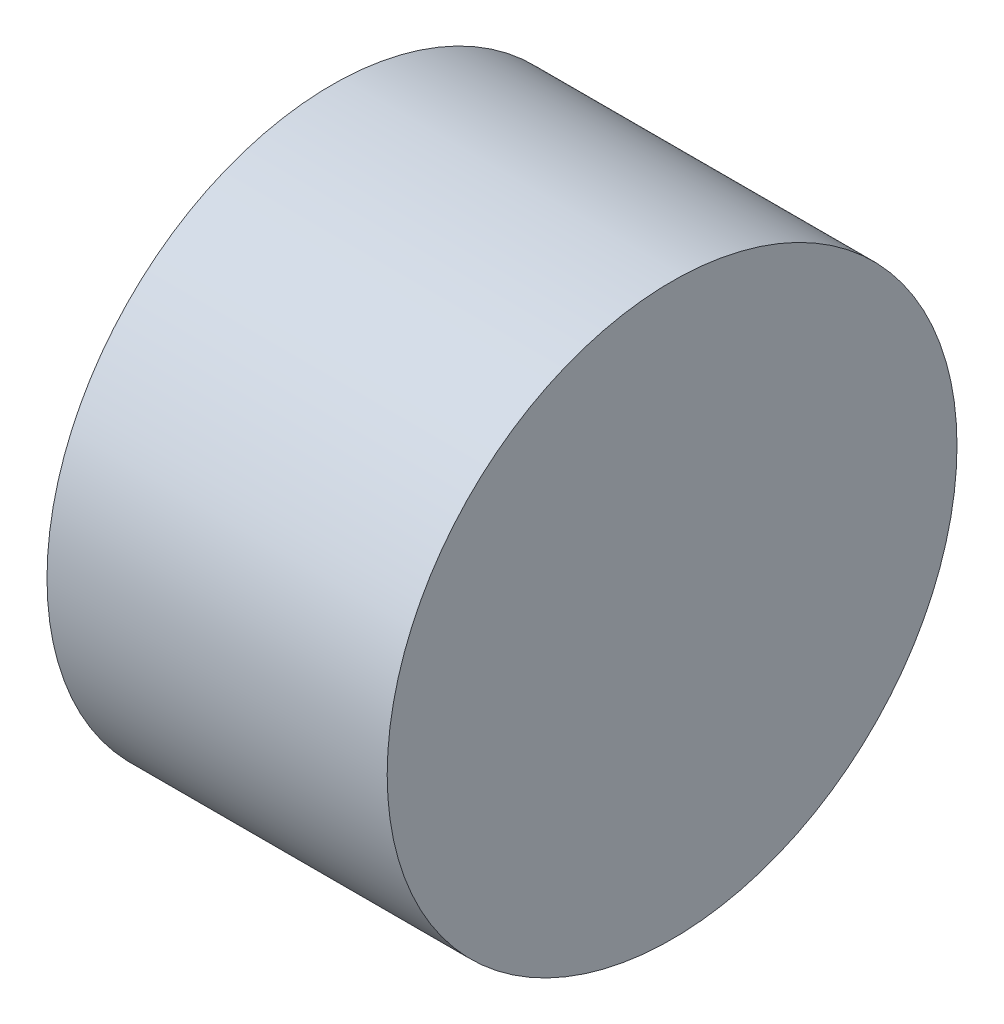
SolidWorks part; units mm, degrees
ref_plane "前视基准面" through (0, 0, 0) normal (0, 0, 1) x (1, 0, 0)
ref_plane "上视基准面" through (0, 0, 0) normal (0, 1, 0) x (1, 0, 0)
ref_plane "右视基准面" through (0, 0, 0) normal (1, 0, 0) x (0, 0, -1)
other "Configuration Table"
sketch "草图1" plane through (0, 0, 0) normal (1, 0, 0) x (0, 0, -1)
  circle A0 centre (0, 0) radius 33.5
  dimension "D1" = 67
extrude "凸台-拉伸1" add sketch "草图1" along normal blind 40
